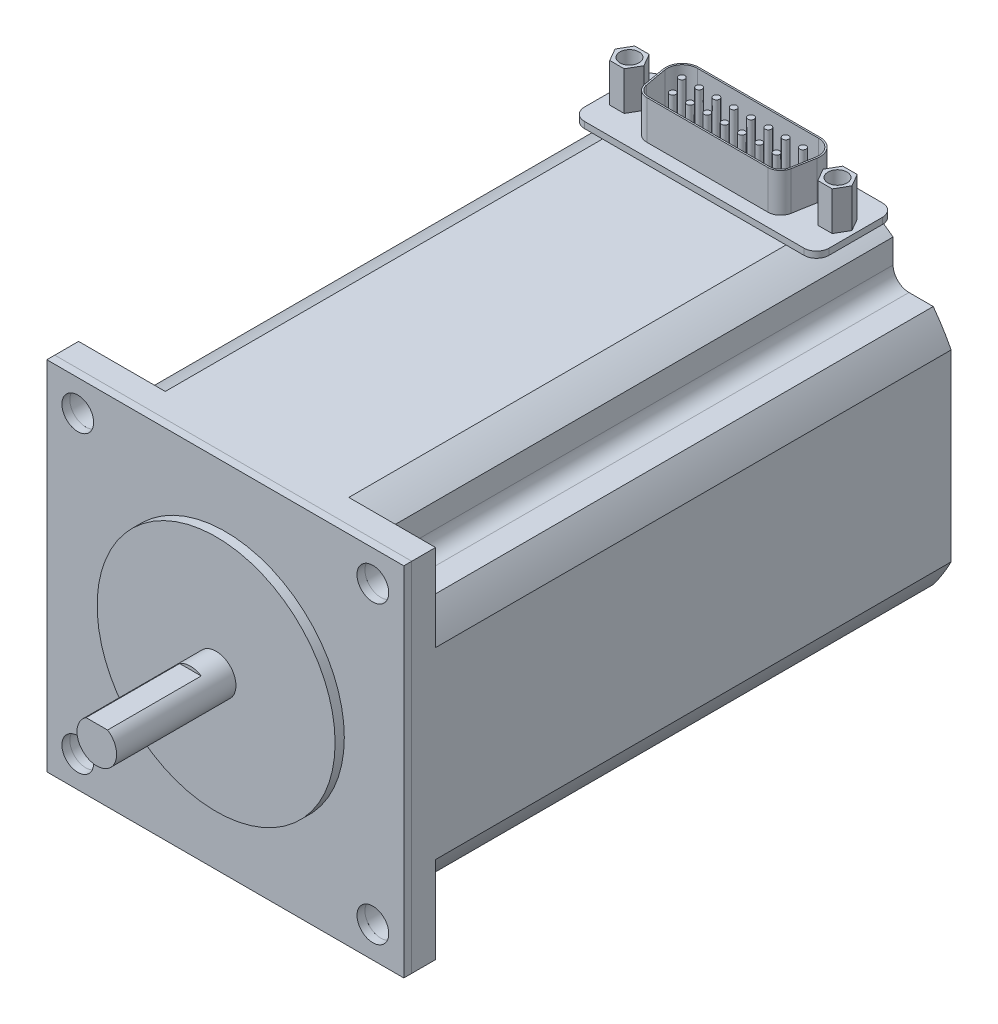
SolidWorks part; units mm, degrees
material "201 Annealed Stainless Steel (SS)"
ref_plane "Front Plane" through (0, 0, 0) normal (0, 0, 1) x (1, 0, 0)
ref_plane "Top Plane" through (0, 0, 0) normal (0, 1, 0) x (1, 0, 0)
ref_plane "Right Plane" through (0, 0, 0) normal (1, 0, 0) x (0, 0, -1)
sketch "Sketch1" plane through (0, 0, 0) normal (0, 0, 1) x (1, 0, 0)
  line L0 (21.8186, 19.2786) -> (25.7048, 19.2786) construction
  line L1 (-28.575, -28.575) -> (28.575, -28.575)
  line L2 (-28.575, -28.575) -> (-28.575, 28.575)
  line L3 (-28.575, 28.575) -> (28.575, 28.575)
  line L4 (28.575, -28.575) -> (28.575, 28.575)
  line L5 (-28.575, -28.575) -> (28.575, 28.575) construction
  line L6 (-28.575, 28.575) -> (28.575, -28.575) construction
  line L7 (23.622, -23.622) -> (-23.622, -23.622) construction
  line L8 (23.622, -23.622) -> (23.622, 23.622) construction
  line L9 (23.622, 23.622) -> (-23.622, 23.622) construction
  line L10 (-23.622, -23.622) -> (-23.622, 23.622) construction
  line L11 (23.622, -23.622) -> (-23.622, 23.622) construction
  line L12 (23.622, 23.622) -> (-23.622, -23.622) construction
  line L13 (-19.2786, 25.7048) -> (-19.2786, 21.8186) construction
  line L14 (-21.8186, 19.2786) -> (-25.7048, 19.2786) construction
  line L15 (-25.7048, -19.2786) -> (-21.8186, -19.2786) construction
  line L16 (-19.2786, -21.8186) -> (-19.2786, -25.7048) construction
  line L17 (19.2786, 25.7048) -> (19.2786, 21.8186) construction
  line L18 (21.8186, 19.2786) -> (23.622, 19.2786) construction
  line L19 (19.2786, -25.7048) -> (19.2786, -21.8186) construction
  line L20 (21.8186, -19.2786) -> (25.7048, -19.2786) construction
  line L21 (-1.7227, 2.667) -> (1.7227, 2.667) construction
  circle A0 centre (-23.622, 23.622) radius 2.54 construction
  circle A1 centre (23.622, 23.622) radius 2.54 construction
  circle A2 centre (23.622, -23.622) radius 2.54 construction
  circle A3 centre (-23.622, -23.622) radius 2.54 construction
  arc A4 (-19.2786, 21.8186) -> (-21.8186, 19.2786) centre (-21.8186, 21.8186) cw construction
  arc A5 (19.2786, 21.8186) -> (21.8186, 19.2786) centre (21.8186, 21.8186) ccw construction
  arc A7 (-21.8186, -19.2786) -> (-19.2786, -21.8186) centre (-21.8186, -21.8186) cw construction
  arc A8 (19.2786, -21.8186) -> (21.8186, -19.2786) centre (21.8186, -21.8186) cw construction
  arc A9 (-19.2786, 25.7048) -> (-14.6925, 28.575) centre (0, 0) cw construction
  arc A10 (19.2786, 25.7048) -> (14.6925, 28.575) centre (0, 0) ccw construction
  arc A11 (25.7048, 19.2786) -> (28.575, 14.6925) centre (0, 0) cw construction
  arc A12 (25.7048, -19.2786) -> (28.575, -14.6925) centre (0, 0) ccw construction
  arc A13 (19.2786, -25.7048) -> (14.6925, -28.575) centre (0, 0) cw construction
  arc A14 (-19.2786, -25.7048) -> (-14.6925, -28.575) centre (0, 0) ccw construction
  arc A15 (-25.7048, -19.2786) -> (-28.575, -14.6925) centre (0, 0) cw construction
  arc A16 (-25.7048, 19.2786) -> (-28.575, 14.6925) centre (0, 0) ccw construction
  circle A17 centre (0, 0) radius 19.05 construction
  circle A18 centre (0, 0) radius 3.175 construction
  point P0 (0, 0)
  point P6 (0, 0)
  point P49 (0, -3.175)
  dimension "D3" = 5.08
  dimension "D5" = 32.131
  dimension "D6" = 2.54
  dimension "D7" = 38.1
  dimension "D8" = 6.35
  dimension "D1" = 57.15
  dimension "D2" = 47.244
  dimension "D4" = 38.5572
  dimension "D9" = 5.842
sketch "Sketch2" plane through (0, 0, 0) normal (0, 0, 1) x (1, 0, 0)
  line L0 (-28.575, -28.575) -> (-28.575, 28.575) construction
  line L1 (-28.575, -28.575) -> (28.575, -28.575) construction
  line L2 (28.575, -28.575) -> (28.575, 28.575) construction
  line L3 (-28.575, 28.575) -> (28.575, 28.575) construction
  line L4 (-28.575, -28.575) -> (-28.575, 28.575)
  line L5 (-28.575, -28.575) -> (28.575, -28.575)
  line L6 (28.575, -28.575) -> (28.575, 28.575)
  line L7 (-28.575, 28.575) -> (28.575, 28.575)
  circle A0 centre (-23.622, -23.622) radius 2.54 construction
  circle A1 centre (-23.622, 23.622) radius 2.54 construction
  circle A2 centre (23.622, 23.622) radius 2.54 construction
  circle A3 centre (23.622, -23.622) radius 2.54 construction
  circle A4 centre (-23.622, -23.622) radius 2.54
  circle A5 centre (-23.622, 23.622) radius 2.54
  circle A6 centre (23.622, 23.622) radius 2.54
  circle A7 centre (23.622, -23.622) radius 2.54
extrude "Body Front" add sketch "Sketch2" along normal blind 3.81
sketch "Sketch3" plane through (0, 0, 3.81) normal (0, 0, 1) x (1, 0, 0)
  line L0 (-28.575, -28.575) -> (-28.575, 28.575) construction
  line L1 (-28.575, -28.575) -> (28.575, -28.575) construction
  line L2 (28.575, -28.575) -> (28.575, 28.575) construction
  line L3 (-28.575, 28.575) -> (28.575, 28.575) construction
  line L4 (-28.575, -28.575) -> (-28.575, 28.575)
  line L5 (-28.575, -28.575) -> (28.575, -28.575)
  line L6 (28.575, -28.575) -> (28.575, 28.575)
  line L7 (-28.575, 28.575) -> (28.575, 28.575)
  circle A0 centre (-23.622, 23.622) radius 2.54 construction
  circle A1 centre (-23.622, -23.622) radius 2.54 construction
  circle A2 centre (23.622, -23.622) radius 2.54 construction
  circle A3 centre (23.622, 23.622) radius 2.54 construction
  circle A4 centre (-23.622, 23.622) radius 2.54
  circle A5 centre (-23.622, -23.622) radius 2.54
  circle A6 centre (23.622, -23.622) radius 2.54
  circle A7 centre (23.622, 23.622) radius 2.54
extrude "Face Plate" add sketch "Sketch3" along normal blind 1.27 separate body
sketch "Sketch4" plane through (0, 0, 0) normal (0, 0, -1) x (-1, 0, 0)
  line L0 (-21.8186, -19.2786) -> (-25.7048, -19.2786) construction
  line L1 (-19.2786, -25.7048) -> (-19.2786, -21.8186) construction
  line L2 (19.2786, -21.8186) -> (19.2786, -25.7048) construction
  line L3 (25.7048, -19.2786) -> (21.8186, -19.2786) construction
  line L4 (21.8186, 19.2786) -> (25.7048, 19.2786) construction
  line L5 (19.2786, 25.7048) -> (19.2786, 21.8186) construction
  line L6 (-21.8186, 19.2786) -> (-25.7048, 19.2786) construction
  line L7 (-19.2786, 25.7048) -> (-19.2786, 21.8186) construction
  line L8 (-21.8186, -19.2786) -> (-25.7048, -19.2786)
  line L9 (-19.2786, -25.7048) -> (-19.2786, -21.8186)
  line L10 (19.2786, -21.8186) -> (19.2786, -25.7048)
  line L11 (25.7048, -19.2786) -> (21.8186, -19.2786)
  line L12 (21.8186, 19.2786) -> (25.7048, 19.2786)
  line L13 (19.2786, 25.7048) -> (19.2786, 21.8186)
  line L14 (-21.8186, 19.2786) -> (-25.7048, 19.2786)
  line L15 (-19.2786, 25.7048) -> (-19.2786, 21.8186)
  line L16 (-14.6925, 28.575) -> (14.6925, 28.575)
  line L17 (28.575, 14.6925) -> (28.575, -14.6925)
  line L18 (14.6925, -28.575) -> (-14.6925, -28.575)
  line L19 (-28.575, -14.6925) -> (-28.575, 14.6925)
  arc A0 (-28.575, -14.6925) -> (-25.7048, -19.2786) centre (0, 0) ccw construction
  arc A1 (-19.2786, -21.8186) -> (-21.8186, -19.2786) centre (-21.8186, -21.8186) ccw construction
  arc A2 (-19.2786, -25.7048) -> (-14.6925, -28.575) centre (0, 0) ccw construction
  arc A3 (14.6925, -28.575) -> (19.2786, -25.7048) centre (0, 0) ccw construction
  arc A4 (21.8186, -19.2786) -> (19.2786, -21.8186) centre (21.8186, -21.8186) ccw construction
  arc A5 (25.7048, -19.2786) -> (28.575, -14.6925) centre (0, 0) ccw construction
  arc A6 (28.575, 14.6925) -> (25.7048, 19.2786) centre (0, 0) ccw construction
  arc A7 (19.2786, 21.8186) -> (21.8186, 19.2786) centre (21.8186, 21.8186) ccw construction
  arc A8 (19.2786, 25.7048) -> (14.6925, 28.575) centre (0, 0) ccw construction
  arc A9 (-25.7048, 19.2786) -> (-28.575, 14.6925) centre (0, 0) ccw construction
  arc A10 (-21.8186, 19.2786) -> (-19.2786, 21.8186) centre (-21.8186, 21.8186) ccw construction
  arc A11 (-14.6925, 28.575) -> (-19.2786, 25.7048) centre (0, 0) ccw construction
  arc A12 (-28.575, -14.6925) -> (-25.7048, -19.2786) centre (0, 0) ccw
  arc A13 (-19.2786, -21.8186) -> (-21.8186, -19.2786) centre (-21.8186, -21.8186) ccw
  arc A14 (-19.2786, -25.7048) -> (-14.6925, -28.575) centre (0, 0) ccw
  arc A15 (14.6925, -28.575) -> (19.2786, -25.7048) centre (0, 0) ccw
  arc A16 (21.8186, -19.2786) -> (19.2786, -21.8186) centre (21.8186, -21.8186) ccw
  arc A17 (25.7048, -19.2786) -> (28.575, -14.6925) centre (0, 0) ccw
  arc A18 (28.575, 14.6925) -> (25.7048, 19.2786) centre (0, 0) ccw
  arc A19 (19.2786, 21.8186) -> (21.8186, 19.2786) centre (21.8186, 21.8186) ccw
  arc A20 (19.2786, 25.7048) -> (14.6925, 28.575) centre (0, 0) ccw
  arc A21 (-25.7048, 19.2786) -> (-28.575, 14.6925) centre (0, 0) ccw
  arc A22 (-21.8186, 19.2786) -> (-19.2786, 21.8186) centre (-21.8186, 21.8186) ccw
  arc A23 (-14.6925, 28.575) -> (-19.2786, 25.7048) centre (0, 0) ccw
extrude "Body Rear" add sketch "Sketch4" along normal offset from surface (82.55 mm away) 87.63 up to face at (26.162, -23.622, 5.08)
sketch "Sketch5" plane through (0, 0, 5.08) normal (0, 0, 1) x (1, 0, 0)
  circle A0 centre (0, 0) radius 19.05 construction
  circle A1 centre (0, 0) radius 19.05
extrude "Shaft Base" add sketch "Sketch5" along normal blind 1.4732 separate body
sketch "Sketch6" plane through (0, 0, 6.5532) normal (0, 0, 1) x (1, 0, 0)
  circle A0 centre (0, 0) radius 3.175 construction
  circle A1 centre (0, 0) radius 3.175
extrude "Shaft" add sketch "Sketch6" along normal offset from surface (19.1008 mm away) 20.574 separate body up to face at (26.162, -23.622, 5.08) offset beyond the face yes
sketch "Sketch7" plane through (0, 0, 25.654) normal (0, 0, 1) x (1, 0, 0)
  line L0 (-1.7227, 2.667) -> (1.7227, 2.667) construction
  line L1 (-1.7227, 2.667) -> (1.7227, 2.667)
  arc A0 (-1.7227, 2.667) -> (1.7227, 2.667) centre (0, 0) cw
  circle M1 centre (0, 0) radius 3.175
extrude "Shaft Flat" cut sketch "Sketch7" against normal blind 14.986 contours L1 M1
sketch "Sketch8" plane through (0, 28.575, 0) normal (0, 1, 0) x (1, 0, 0)
  line L0 (-17.57, 82.55) -> (17.57, 82.55)
  line L1 (19.57, 80.55) -> (19.57, 72)
  line L2 (17.57, 70) -> (-17.57, 70)
  line L3 (-19.57, 72) -> (-19.57, 80.55)
  line L4 (14.6925, 82.55) -> (-14.6925, 82.55) construction
  line L5 (-11.7074, 73.7836) -> (-12.33, 77.3147)
  line L6 (-9.695, 80.455) -> (9.695, 80.455)
  line L7 (12.33, 77.3147) -> (11.7074, 73.7836)
  line L8 (9.695, 72.095) -> (-9.695, 72.095)
  line L9 (0, 80.455) -> (0, 72.095) construction
  line L10 (-16.655, 76.275) -> (16.655, 76.275) construction
  line L11 (-9.695, 77.695) -> (-8.31, 74.855) construction
  line L12 (-9.695, 77.695) -> (-6.9239, 77.695) construction
  line L13 (-8.31, 74.855) -> (-5.5389, 74.855) construction
  line L14 (-9.695, 80.205) -> (9.695, 80.205)
  line L15 (12.0838, 77.3581) -> (11.4612, 73.827)
  line L16 (9.695, 72.345) -> (-9.695, 72.345)
  line L17 (-11.4612, 73.827) -> (-12.0838, 77.3581)
  line L19 (-15.5003, 78.275) -> (-17.8097, 78.275)
  line L20 (-17.8097, 78.275) -> (-18.9644, 76.275)
  line L21 (-18.9644, 76.275) -> (-17.8097, 74.275)
  line L22 (-17.8097, 74.275) -> (-15.5003, 74.275)
  line L23 (-15.5003, 74.275) -> (-14.3456, 76.275)
  line L24 (-14.3456, 76.275) -> (-15.5003, 78.275)
  line L25 (17.8097, 74.275) -> (18.9644, 76.275)
  line L26 (18.9644, 76.275) -> (17.8097, 78.275)
  line L27 (17.8097, 78.275) -> (15.5003, 78.275)
  line L28 (15.5003, 78.275) -> (14.3456, 76.275)
  line L29 (14.3456, 76.275) -> (15.5003, 74.275)
  line L30 (15.5003, 74.275) -> (17.8097, 74.275)
  arc A0 (17.57, 82.55) -> (19.57, 80.55) centre (17.57, 80.55) cw
  arc A1 (19.57, 72) -> (17.57, 70) centre (17.57, 72) cw
  arc A2 (-17.57, 70) -> (-19.57, 72) centre (-17.57, 72) cw
  arc A3 (-19.57, 80.55) -> (-17.57, 82.55) centre (-17.57, 80.55) cw
  arc A4 (-12.33, 77.3147) -> (-9.695, 80.455) centre (-9.695, 77.7794) cw
  arc A5 (9.695, 80.455) -> (12.33, 77.3147) centre (9.695, 77.7794) cw
  arc A6 (11.7074, 73.7836) -> (9.695, 72.095) centre (9.695, 74.1384) cw
  arc A7 (-9.695, 72.095) -> (-11.7074, 73.7836) centre (-9.695, 74.1384) cw
  circle A8 centre (-16.655, 76.275) radius 1.525
  circle A9 centre (16.655, 76.275) radius 1.525
  circle A10 centre (-9.695, 77.695) radius 0.5
  circle A11 centre (-8.31, 74.855) radius 0.5
  circle A12 centre (-6.9239, 77.695) radius 0.5
  circle A13 centre (-4.1527, 77.695) radius 0.5
  circle A14 centre (-1.3816, 77.695) radius 0.5
  circle A15 centre (1.3896, 77.695) radius 0.5
  circle A16 centre (4.1607, 77.695) radius 0.5
  circle A17 centre (6.9318, 77.695) radius 0.5
  circle A18 centre (9.703, 77.695) radius 0.5
  circle A19 centre (-5.5389, 74.855) radius 0.5
  circle A20 centre (-2.7677, 74.855) radius 0.5
  circle A21 centre (0.0034, 74.855) radius 0.5
  circle A22 centre (2.7746, 74.855) radius 0.5
  circle A23 centre (5.5457, 74.855) radius 0.5
  circle A24 centre (8.3168, 74.855) radius 0.5
  arc A25 (9.695, 80.205) -> (12.0838, 77.3581) centre (9.695, 77.7794) cw
  arc A26 (11.4612, 73.827) -> (9.695, 72.345) centre (9.695, 74.1384) cw
  arc A27 (-9.695, 72.345) -> (-11.4612, 73.827) centre (-9.695, 74.1384) cw
  arc A28 (-12.0838, 77.3581) -> (-9.695, 80.205) centre (-9.695, 77.7794) cw
  circle A29 centre (-16.655, 76.275) radius 2 construction
  circle A30 centre (16.655, 76.275) radius 2 construction
  point P13 (0, 70)
  point P28 (0, 76.275)
  point P30 (-19.57, 76.275)
  point P32 (0, 72.095)
  point P36 (-9.0025, 76.275)
  point P37 (0, 76.275)
  dimension "D3" = 2
  dimension "D9" = 3.05
  dimension "D11" = 1
  dimension "D1" = 39.14
  dimension "D2" = 12.55
  dimension "D4" = 10
  dimension "D5" = 8.36
  dimension "D6" = 10
  dimension "D7" = 24.66
  dimension "D8" = 19.39
  dimension "D10" = 33.31
  dimension "D12" = 2.84
  dimension "D13" = 1.385
  dimension "D16" = 2.7711
  dimension "D17" = 2.7711
  dimension "D19" = 4
  dimension "D18" = 0.25
  dimension "D14" = 8
  dimension "D15" = 7
sketch "Sketch9" plane through (0, 28.575, 0) normal (0, 1, 0) x (1, 0, 0)
  line L0 (-19.57, 72) -> (-19.57, 80.55) construction
  line L1 (17.57, 70) -> (-17.57, 70) construction
  line L2 (19.57, 80.55) -> (19.57, 72) construction
  line L3 (-17.57, 82.55) -> (17.57, 82.55) construction
  line L4 (-19.57, 72) -> (-19.57, 80.55)
  line L5 (17.57, 70) -> (-17.57, 70)
  line L6 (19.57, 80.55) -> (19.57, 72)
  line L7 (-17.57, 82.55) -> (17.57, 82.55)
  arc A0 (-17.57, 82.55) -> (-19.57, 80.55) centre (-17.57, 80.55) ccw construction
  arc A1 (-19.57, 72) -> (-17.57, 70) centre (-17.57, 72) ccw construction
  arc A2 (17.57, 70) -> (19.57, 72) centre (17.57, 72) ccw construction
  arc A3 (19.57, 80.55) -> (17.57, 82.55) centre (17.57, 80.55) ccw construction
  arc A4 (-17.57, 82.55) -> (-19.57, 80.55) centre (-17.57, 80.55) ccw
  arc A5 (-19.57, 72) -> (-17.57, 70) centre (-17.57, 72) ccw
  arc A6 (17.57, 70) -> (19.57, 72) centre (17.57, 72) ccw
  arc A7 (19.57, 80.55) -> (17.57, 82.55) centre (17.57, 80.55) ccw
  circle A8 centre (16.655, 76.275) radius 1.525 construction
  circle A9 centre (-16.655, 76.275) radius 1.525 construction
  circle A10 centre (16.655, 76.275) radius 1.525
  circle A11 centre (-16.655, 76.275) radius 1.525
extrude "Connector Base" add sketch "Sketch9" along normal blind 1 separate body
sketch "Sketch10" plane through (0, 29.575, 0) normal (0, 1, 0) x (1, 0, 0)
  line L0 (14.3456, 76.275) -> (15.5003, 74.275) construction
  line L1 (15.5003, 74.275) -> (17.8097, 74.275) construction
  line L2 (17.8097, 74.275) -> (18.9644, 76.275) construction
  line L3 (18.9644, 76.275) -> (17.8097, 78.275) construction
  line L4 (17.8097, 78.275) -> (15.5003, 78.275) construction
  line L5 (15.5003, 78.275) -> (14.3456, 76.275) construction
  line L6 (-15.5003, 74.275) -> (-14.3456, 76.275) construction
  line L7 (-14.3456, 76.275) -> (-15.5003, 78.275) construction
  line L8 (-17.8097, 74.275) -> (-15.5003, 74.275) construction
  line L9 (-18.9644, 76.275) -> (-17.8097, 74.275) construction
  line L10 (-17.8097, 78.275) -> (-18.9644, 76.275) construction
  line L11 (-15.5003, 78.275) -> (-17.8097, 78.275) construction
  line L12 (14.3456, 76.275) -> (15.5003, 74.275)
  line L13 (15.5003, 74.275) -> (17.8097, 74.275)
  line L14 (17.8097, 74.275) -> (18.9644, 76.275)
  line L15 (18.9644, 76.275) -> (17.8097, 78.275)
  line L16 (17.8097, 78.275) -> (15.5003, 78.275)
  line L17 (15.5003, 78.275) -> (14.3456, 76.275)
  line L18 (-15.5003, 74.275) -> (-14.3456, 76.275)
  line L19 (-14.3456, 76.275) -> (-15.5003, 78.275)
  line L20 (-17.8097, 74.275) -> (-15.5003, 74.275)
  line L21 (-18.9644, 76.275) -> (-17.8097, 74.275)
  line L22 (-17.8097, 78.275) -> (-18.9644, 76.275)
  line L23 (-15.5003, 78.275) -> (-17.8097, 78.275)
  line L24 (-11.7074, 73.7836) -> (-12.33, 77.3147) construction
  line L25 (-9.695, 80.205) -> (9.695, 80.205) construction
  line L26 (12.0838, 77.3581) -> (11.4612, 73.827) construction
  line L27 (9.695, 72.345) -> (-9.695, 72.345) construction
  line L28 (-11.4612, 73.827) -> (-12.0838, 77.3581) construction
  line L29 (-9.695, 80.455) -> (9.695, 80.455) construction
  line L30 (12.33, 77.3147) -> (11.7074, 73.7836) construction
  line L31 (9.695, 72.095) -> (-9.695, 72.095) construction
  line L32 (-9.695, 80.455) -> (9.695, 80.455)
  line L33 (12.33, 77.3147) -> (11.7074, 73.7836)
  line L34 (9.695, 72.095) -> (-9.695, 72.095)
  line L35 (-11.7074, 73.7836) -> (-12.33, 77.3147)
  line L36 (-11.4612, 73.827) -> (-12.0838, 77.3581)
  line L37 (9.695, 72.345) -> (-9.695, 72.345)
  line L38 (12.0838, 77.3581) -> (11.4612, 73.827)
  line L39 (-9.695, 80.205) -> (9.695, 80.205)
  circle A0 centre (16.655, 76.275) radius 1.525 construction
  circle A1 centre (-16.655, 76.275) radius 1.525 construction
  circle A2 centre (16.655, 76.275) radius 1.525
  circle A3 centre (-16.655, 76.275) radius 1.525
  arc A4 (-9.695, 80.205) -> (-12.0838, 77.3581) centre (-9.695, 77.7794) ccw construction
  arc A5 (12.0838, 77.3581) -> (9.695, 80.205) centre (9.695, 77.7794) ccw construction
  arc A6 (9.695, 72.345) -> (11.4612, 73.827) centre (9.695, 74.1384) ccw construction
  arc A7 (-11.4612, 73.827) -> (-9.695, 72.345) centre (-9.695, 74.1384) ccw construction
  arc A8 (-9.695, 80.455) -> (-12.33, 77.3147) centre (-9.695, 77.7794) ccw construction
  arc A9 (12.33, 77.3147) -> (9.695, 80.455) centre (9.695, 77.7794) ccw construction
  arc A10 (9.695, 72.095) -> (11.7074, 73.7836) centre (9.695, 74.1384) ccw construction
  arc A11 (-11.7074, 73.7836) -> (-9.695, 72.095) centre (-9.695, 74.1384) ccw construction
  arc A12 (-9.695, 80.455) -> (-12.33, 77.3147) centre (-9.695, 77.7794) ccw
  arc A13 (12.33, 77.3147) -> (9.695, 80.455) centre (9.695, 77.7794) ccw
  arc A14 (9.695, 72.095) -> (11.7074, 73.7836) centre (9.695, 74.1384) ccw
  arc A15 (-11.7074, 73.7836) -> (-9.695, 72.095) centre (-9.695, 74.1384) ccw
  arc A16 (-11.4612, 73.827) -> (-9.695, 72.345) centre (-9.695, 74.1384) ccw
  arc A17 (9.695, 72.345) -> (11.4612, 73.827) centre (9.695, 74.1384) ccw
  arc A18 (12.0838, 77.3581) -> (9.695, 80.205) centre (9.695, 77.7794) ccw
  arc A19 (-9.695, 80.205) -> (-12.0838, 77.3581) centre (-9.695, 77.7794) ccw
  circle A20 centre (2.7746, 74.855) radius 0.5 construction
  circle A21 centre (5.5457, 74.855) radius 0.5 construction
  circle A22 centre (8.3168, 74.855) radius 0.5 construction
  circle A23 centre (9.703, 77.695) radius 0.5 construction
  circle A24 centre (6.9318, 77.695) radius 0.5 construction
  circle A25 centre (4.1607, 77.695) radius 0.5 construction
  circle A26 centre (1.3896, 77.695) radius 0.5 construction
  circle A27 centre (-1.3816, 77.695) radius 0.5 construction
  circle A28 centre (0.0034, 74.855) radius 0.5 construction
  circle A29 centre (-2.7677, 74.855) radius 0.5 construction
  circle A30 centre (-4.1527, 77.695) radius 0.5 construction
  circle A31 centre (-8.31, 74.855) radius 0.5 construction
  circle A32 centre (-5.5389, 74.855) radius 0.5 construction
  circle A33 centre (-6.9239, 77.695) radius 0.5 construction
  circle A34 centre (-9.695, 77.695) radius 0.5 construction
  circle A35 centre (2.7746, 74.855) radius 0.5
  circle A36 centre (5.5457, 74.855) radius 0.5
  circle A37 centre (8.3168, 74.855) radius 0.5
  circle A38 centre (9.703, 77.695) radius 0.5
  circle A39 centre (6.9318, 77.695) radius 0.5
  circle A40 centre (4.1607, 77.695) radius 0.5
  circle A41 centre (1.3896, 77.695) radius 0.5
  circle A42 centre (-1.3816, 77.695) radius 0.5
  circle A43 centre (0.0034, 74.855) radius 0.5
  circle A44 centre (-2.7677, 74.855) radius 0.5
  circle A45 centre (-4.1527, 77.695) radius 0.5
  circle A46 centre (-8.31, 74.855) radius 0.5
  circle A47 centre (-5.5389, 74.855) radius 0.5
  circle A48 centre (-6.9239, 77.695) radius 0.5
  circle A49 centre (-9.695, 77.695) radius 0.5
  circle M16 centre (16.655, 76.275) radius 1.525
  circle M25 centre (-16.655, 76.275) radius 1.525
extrude "Connector" add sketch "Sketch10" along normal offset from surface (6.2 mm away) 7.2 contours L19 L23 L22 L21 L20 L18 M25 | L35 A15 L34 A14 L33 A13 L32 A12 A19 L39 A18 L38 A17 L37 A16 L36 | A49 | A48 | A46 | A47 | A44 | A45 | A43 | A41 | A35 | A40 | A36 | A39 | A37 | A38 | L16 L17 L12 L13 L14 L15 M16 | A42 up to face at (0, 28.575, -19.685) offset beyond the face yes
scale "Scale1" bodies to scale 111 107 109 105 106 scale about origin uniform scaling yes scale factor 2
scale "Scale2" bodies to scale 113 116 114 112 115 scale about origin uniform scaling yes scale factor 0.1
scale "Scale3" bodies to scale 119 121 117 120 118 scale about origin uniform scaling yes scale factor 3
equation "\"D6@Sketch8\"=\"D4@Sketch8\""
